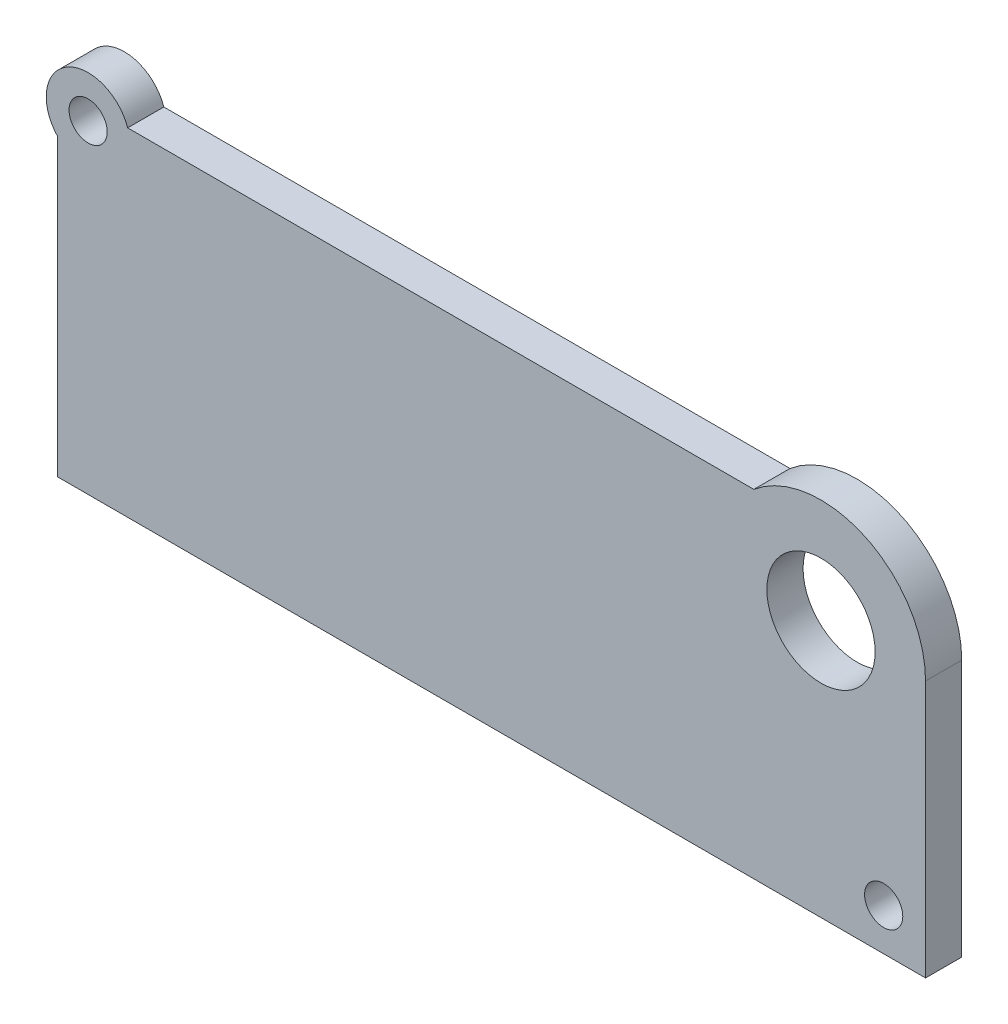
SolidWorks part; units mm, degrees
ref_plane "Front Plane" through (0, 0, 0) normal (0, 0, 1) x (1, 0, 0)
ref_plane "Top Plane" through (0, 0, 0) normal (0, 1, 0) x (1, 0, 0)
ref_plane "Right Plane" through (0, 0, 0) normal (1, 0, 0) x (0, 0, -1)
sketch "Sketch1" plane through (0, 0, 0) normal (0, 0, 1) x (1, 0, 0)
  line L1 (-26.416, -9.8) -> (26.416, -9.8)
  line L2 (-26.416, -9.8) -> (-26.416, 9.8)
  line L3 (-26.416, 9.8) -> (26.416, 9.8)
  line L4 (26.416, -9.8) -> (26.416, 9.8)
  line L5 (-26.416, -9.8) -> (26.416, 9.8) construction
  line L6 (-26.416, 9.8) -> (26.416, -9.8) construction
  line L7 (-20.15, -9.8) -> (20.15, -9.8)
  line L8 (-20.15, -9.8) -> (-20.15, 9.8)
  line L9 (-20.15, 9.8) -> (20.15, 9.8)
  line L10 (20.15, -9.8) -> (20.15, 9.8)
  line L11 (-20.15, -9.8) -> (20.15, 9.8) construction
  line L12 (-20.15, 9.8) -> (20.15, -9.8) construction
  line L13 (-26.416, 9.8) -> (26.416, 9.8)
  line L14 (-26.416, 9.8) -> (-26.416, 14.8)
  line L15 (-26.416, 14.8) -> (26.416, 14.8)
  line L16 (26.416, 9.8) -> (26.416, 14.8)
  line L17 (26.416, -9.8) -> (-26.416, -9.8)
  line L18 (26.416, -9.8) -> (26.416, -14.8)
  line L19 (26.416, -14.8) -> (-26.416, -14.8)
  line L20 (-26.416, -9.8) -> (-26.416, -14.8)
  circle A0 centre (-23.95, -4.974) radius 1.675
  circle A1 centre (-23.95, 4.974) radius 1.675
  circle A2 centre (23.95, 4.974) radius 1.675
  circle A3 centre (23.95, -4.974) radius 1.675
  point P0 (0, 0)
  point P14 (0, 0)
  dimension "D1" = 3.35
  dimension "D2" = 3.35
  dimension "D3" = 3.35
  dimension "D4" = 3.35
  dimension "D7" = 4.826
  dimension "D8" = 3.8
  dimension "D9" = 3.8
  dimension "D10" = 4.826
  dimension "D11" = 4.826
  dimension "D12" = 4.826
  dimension "D13" = 3.8
  dimension "D5" = 19.6
  dimension "D6" = 52.832
  dimension "D15" = 40.3
  dimension "D16" = 5
  dimension "D17" = 5
  dimension "3.9" = 3.8
extrude "Boss-Extrude2" add sketch "Sketch1" along normal blind 3.175 contours L1 L8 L3 L2 A1 A0 | L1 L20 L19 L18 | L3 L16 L15 L14 | L10 L1 L4 L3 A3 A2
sketch "Sketch3" plane through (0, 0, 3.175) normal (0, 0, 1) x (1, 0, 0)
  line L0 (26.416, -14.8) -> (56.416, -14.8)
  line L6 (26.416, 14.8) -> (56.416, 14.8)
  line L7 (26.416, 14.8) -> (26.416, -14.906)
  line L8 (26.416, -14.906) -> (56.416, -14.906)
  line L9 (56.416, 14.8) -> (56.416, -14.906)
  line M3 (26.416, -14.8) -> (26.416, 14.8)
  dimension "D2" = 30
extrude "Boss-Extrude3" add sketch "Sketch3" against normal up to surface (3.175 mm away) contours L9 L6 L0 M3 up to face at (0, 0, 0)
sketch "Sketch4" plane through (0, 0, 0) normal (0, 0, -1) x (-1, 0, 0)
  line L3 (-56.416, 14.8) -> (-56.416, -14.8) construction
  line L4 (-56.416, -14.8) -> (26.416, -14.8) construction
  circle A0 centre (-40.576, 7.77) radius 4.75
  dimension "D1" = 15.84
  dimension "D2" = 22.57
  dimension "D3" = 9.5
extrude "Cut-Extrude1" cut sketch "Sketch4" against normal blind 10 contours A0
sketch "Sketch22" plane through (0, 0, 0) normal (0, 0, -1) x (-1, 0, 0)
  line L0 (-52.3294, 14.8) -> (-30.0917, 14.8)
  line L1 (26.416, 14.8) -> (-56.416, 14.8) construction
  circle A0 centre (-40.576, 7.77) radius 9.175
  dimension "D1" = 18.35
extrude "Boss-Extrude14" add sketch "Sketch22" against normal up to surface (3.175 mm away) contours L0 A0
sketch "Sketch23" plane through (0, 0, 0) normal (0, 0, -1) x (-1, 0, 0)
  line L0 (-49.751, 7.77) -> (-49.751, -14.8)
  line L1 (-56.416, -14.8) -> (26.416, -14.8) construction
  circle A0 centre (-40.576, 7.77) radius 9.175
  line M4 (-46.4717, 14.8) -> (-56.416, 14.8)
  line M5 (-56.416, 14.8) -> (-56.416, -14.8)
  line M6 (-56.416, -14.8) -> (26.416, -14.8)
extrude "Cut-Extrude8" cut sketch "Sketch23" against normal blind 10 contours A0 L0 M4 M5 M6
sketch "Sketch24" plane through (0, 0, 0) normal (0, 0, -1) x (-1, 0, 0)
  line L1 (26.416, 14.8) -> (-34.6803, 14.8) construction
  line L2 (26.416, -14.8) -> (26.416, 14.8) construction
  circle A0 centre (23.736, 13.59) radius 1.675
  dimension "D1" = 3.35
  dimension "D2" = 1.21
  dimension "D3" = 2.68
extrude "Cut-Extrude9" cut sketch "Sketch24" against normal blind 10
sketch "Sketch25" plane through (0, 0, 0) normal (0, 0, -1) x (-1, 0, 0)
  circle A0 centre (23.736, 13.59) radius 1.675
  circle A1 centre (23.95, 4.974) radius 1.675
  circle A2 centre (23.95, -4.974) radius 1.675
  circle A7 centre (23.95, -4.974) radius 3.675
  circle A8 centre (23.95, 4.974) radius 3.675
  circle A9 centre (23.736, 13.59) radius 3.675
  dimension "D1" = 2
  dimension "D2" = 2
extrude "Boss-Extrude15" add sketch "Sketch25" against normal up to surface (3.175 mm away) up to face at (5.1596, 5.6121, 3.175)
sketch "Sketch26" plane through (0, 0, 0) normal (0, 0, -1) x (-1, 0, 0)
  line L0 (-49.751, -14.8) -> (26.416, -14.8) construction
  line L2 (-49.751, 7.77) -> (-49.751, -14.8) construction
  circle A0 centre (-46.076, -11.125) radius 1.675
  circle A1 centre (-46.076, -11.125) radius 3.675
  dimension "D1" = 3.35
  dimension "D2" = 3.675
  dimension "D3" = 3.675
  dimension "D4" = 2
extrude "Cut-Extrude12" cut sketch "Sketch26" against normal up to surface (3.175 mm away) contours A0 up to face at (-4.7057, 2.7441, 3.175)
sketch "Sketch27" plane through (0, 0, 0) normal (0, 0, -1) x (-1, 0, 0)
  line L1 (-26.8834, 11.0214) -> (26.0491, 11.0214)
  line L2 (-26.8834, 11.0214) -> (-26.8834, -11.9842)
  line L3 (-26.8834, -11.9842) -> (26.0491, -11.9842)
  line L4 (26.0491, 11.0214) -> (26.0491, -11.9842)
extrude "Boss-Extrude16" add sketch "Sketch27" against normal up to surface (3.175 mm away) up to face at (47.751, -11.125, 3.175)
sketch "Sketch28" plane through (0, 0, 0) normal (0, 0, -1) x (-1, 0, 0)
  line L0 (26.416, 8.9779) -> (26.416, -8.886)
  line L1 (26.416, 7.6988) -> (26.416, 11.0754) construction
  line L2 (26.416, -14.8) -> (26.416, -7.6988) construction
  line L3 (26.416, -8.886) -> (33.6957, -3.4148)
  line L4 (33.6957, -3.4148) -> (26.416, 8.9779)
extrude "Cut-Extrude14" cut sketch "Sketch28" against normal blind 10
